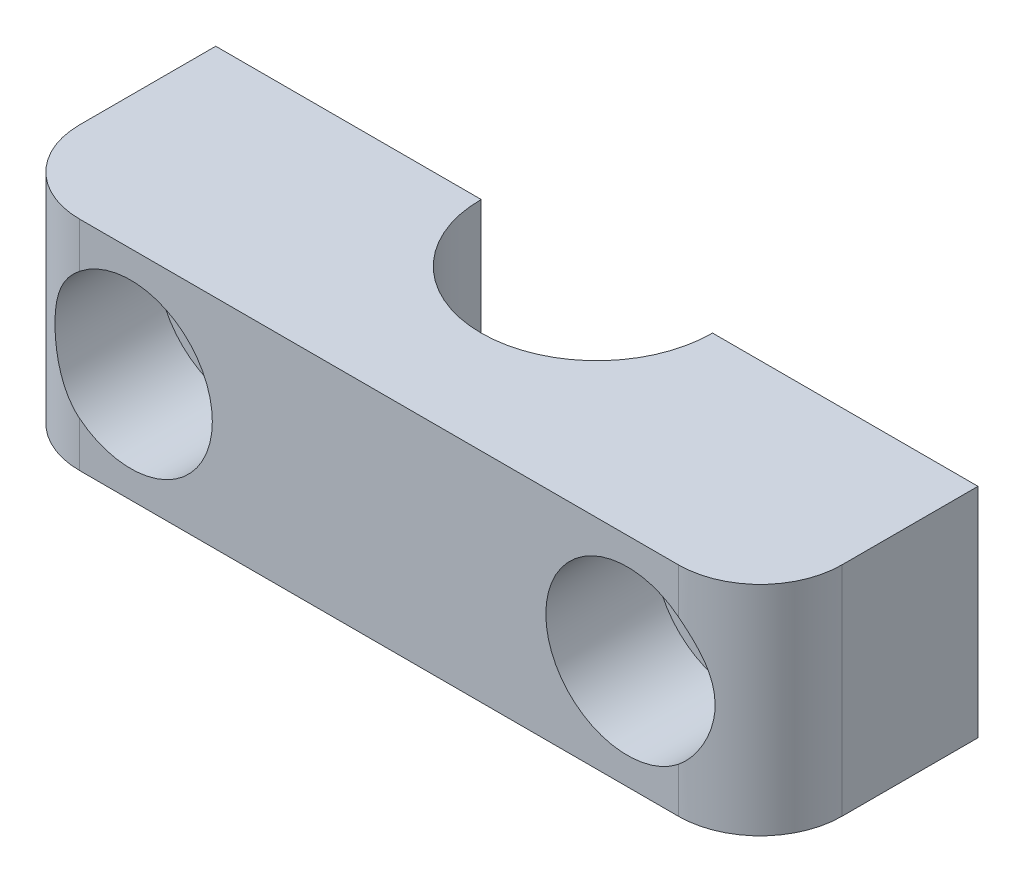
SolidWorks part; units mm, degrees
ref_plane "Front Plane" through (0, 0, 0) normal (0, 0, 1) x (1, 0, 0)
ref_plane "Top Plane" through (0, 0, 0) normal (0, 1, 0) x (1, 0, 0)
ref_plane "Right Plane" through (0, 0, 0) normal (1, 0, 0) x (0, 0, -1)
sketch "Sketch2" plane through (0, 0, 0) normal (0, 0, -1) x (1, 0, 0)
  line L1 (0, 31) -> (28, 31)
  line L2 (0, 31) -> (0, 23)
  line L3 (0, 23) -> (28, 23)
  line L4 (28, 31) -> (28, 23)
  dimension "D1" = 8
  dimension "D2" = 28
extrude "BridgeBoss-Extrude2" add sketch "Sketch2" along normal blind 8
sketch "Sketch3" plane through (0, -23, 0) normal (0, 1, 0) x (1, 0, 0)
  line L0 (0, 8) -> (28, 8) construction
  line L2 (9.75, 8) -> (18.25, 8)
  line L3 (0, 8) -> (0, 0) construction
  arc A0 (18.25, 8) -> (9.75, 8) centre (14, 8) cw
  dimension "D1" = 8.5
  dimension "D2" = 14
  dimension "D3" = 9.75
extrude "GrommetCut-Extrude3" cut sketch "Sketch3" against normal through all
sketch "BridgeMountHolesSketch4" plane through (0, 0, -8) normal (0, 0, -1) x (1, 0, 0)
  line L0 (0, 31) -> (9.75, 23) construction
  line L1 (18.25, 31) -> (28, 23) construction
  circle A0 centre (4.875, 27) radius 1.55
  circle A1 centre (23.125, 27) radius 1.55
  dimension "D1" = 3.1
  dimension "D2" = 18.25
extrude "BridgeMountholesCut-Extrude4" cut sketch "BridgeMountHolesSketch4" against normal through all
fillet "Fillet1" radius 3 2 edges at (28, -27, 0) (0, -27, 0)
sketch "Sketch4" plane through (0, 0, 0) normal (0, 0, 1) x (1, 0, 0)
  circle A0 centre (4.875, -27) radius 3
  circle A1 centre (23.125, -27) radius 3
  dimension "D1" = 6
extrude "MountHolesBoreCut-Extrude1" cut sketch "Sketch4" against normal blind 4
equation "\"DragChainHeight\"= 28mm"
equation "\"DragChainBridgeHeight\"= 8mm"
equation "\"DragChainBuildPlateBridgeWidth\"= 8mm"
equation "\"D1@Sketch2\"=\"DragChainBuildPlateBridgeWidth\""
equation "\"D1@BridgeBoss-Extrude2\"=\"DragChainBridgeHeight\""
equation "\"D2@Sketch3\"=\"DragChainHeight\"/2"
equation "\"M3HoleDiameter\"= 3.1mm'Add .1mm for printing"
equation "\"D1@BridgeMountHolesSketch4\"=\"M3HoleDiameter\""
equation "\"GrommetHoleDiameter\"= 8.5"
equation "\"M3ButtonHeadDiameter\"= 6mm"
equation "\"M3ButtonHeadDepth\"=4"
equation "\"D1@MountHolesBoreCut-Extrude1\" = \"M3ButtonHeadDepth\""
equation "\"D1@Sketch3\"=\"GrommetHoleDiameter\""
equation "\"D2@Sketch2\"=\"DragChainHeight\""
equation "\"D1@Sketch4\"=\"M3ButtonHeadDiameter\""
